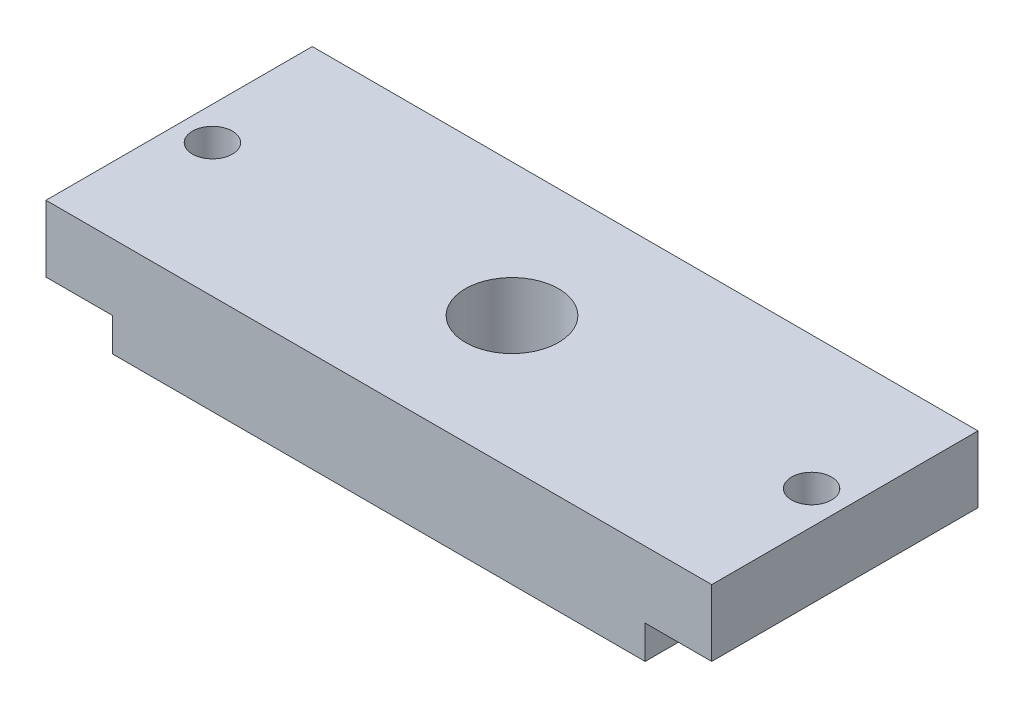
SolidWorks part; units mm, degrees
ref_plane "Plan de face" through (0, 0, 0) normal (0, 0, 1) x (1, 0, 0)
ref_plane "Plan de dessus" through (0, 0, 0) normal (0, 1, 0) x (1, 0, 0)
ref_plane "Plan de droite" through (0, 0, 0) normal (1, 0, 0) x (0, 0, -1)
sketch "Esquisse1" plane through (0, 0, 0) normal (0, 0, 1) x (1, 0, 0)
  line L0 (0, 0) -> (-50, 0)
  line L1 (-50, 0) -> (-50, -5)
  line L2 (-50, -5) -> (-45, -5)
  line L3 (-45, -5) -> (-45, -7.5)
  line L4 (-45, -7.5) -> (-5, -7.5)
  line L5 (-5, -7.5) -> (-5, -5)
  line L6 (-5, -5) -> (0, -5)
  line L7 (0, -5) -> (0, 0)
  line L8 (-25, 0) -> (-25, -7.5) construction
  dimension "D1" = 40
  dimension "D2" = 5
  dimension "D3" = 5
  dimension "D4" = 2.5
  dimension "D5" = 5
extrude "Extrusion1" add sketch "Esquisse1" along normal blind 20
sketch "Esquisse2" plane through (0, 0, 0) normal (0, 1, 0) x (1, 0, 0)
  line L0 (-25, -10) -> (-25, -20) construction
  line L1 (0, -20) -> (-50, -20) construction
  line L2 (-25, -10) -> (0, -10) construction
  line L3 (0, -20) -> (0, 0) construction
  circle A0 centre (-25, -10) radius 3.5
  dimension "D1" = 7
extrude "Enlèv. mat.-Extru.1" cut sketch "Esquisse2" against normal blind 20
sketch "Esquisse3" plane through (0, -5, 0) normal (0, -1, 0) x (1, 0, 0)
  line L0 (-50, 20) -> (-45, 0) construction
  line L1 (-25, 13.5) -> (-25, 6.5) construction
  line L2 (-50, 20) -> (-50, 0) construction
  circle A0 centre (-47.5, 10) radius 1.5
  circle A1 centre (-25, 10) radius 3.5 construction
  circle A2 centre (-2.5, 10) radius 1.5
  point P13 (-50, 10)
  dimension "D1" = 3
  dimension "D2" = 45
  dimension "D3" = 2.5
extrude "Enlèv. mat.-Extru.2" cut sketch "Esquisse3" against normal blind 10
